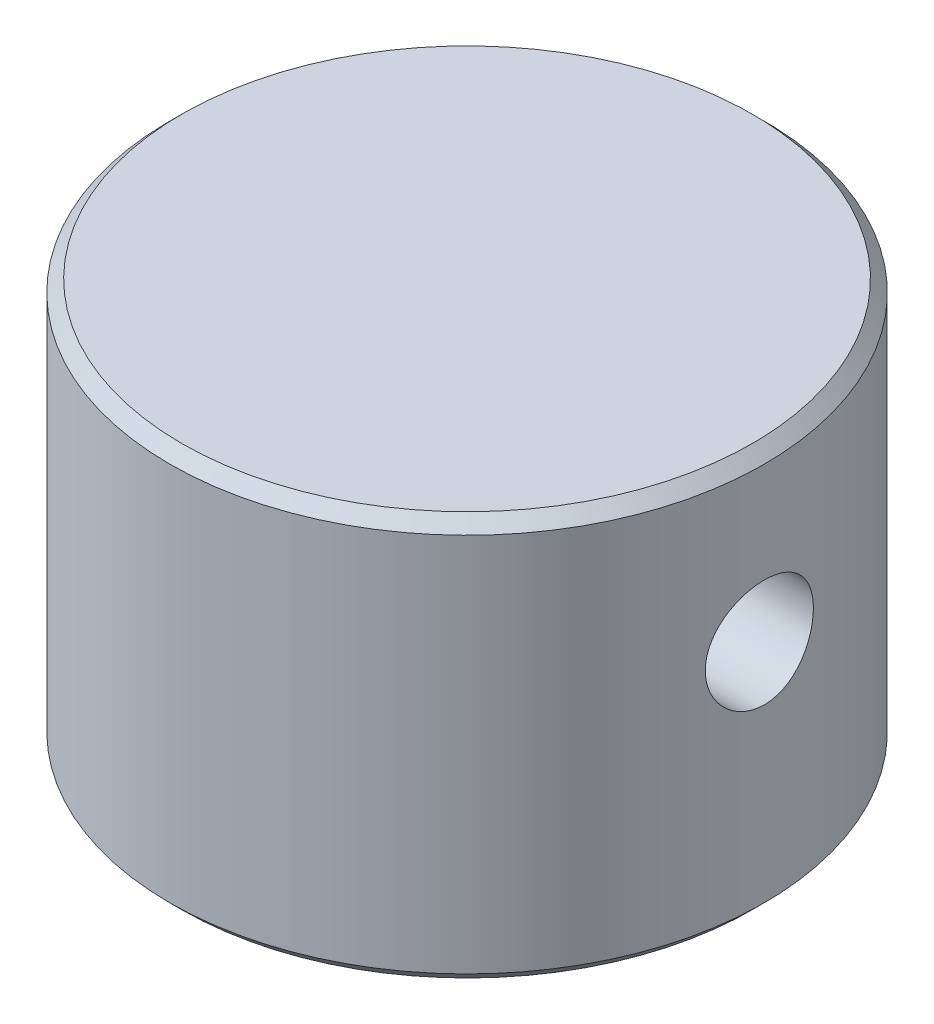
SolidWorks part; units mm, degrees
material "ASTM A36 Steel"
ref_plane "Front Plane" through (0, 0, 0) normal (0, 0, 1) x (1, 0, 0)
ref_plane "Top Plane" through (0, 0, 0) normal (0, 1, 0) x (1, 0, 0)
ref_plane "Right Plane" through (0, 0, 0) normal (1, 0, 0) x (0, 0, -1)
sketch "Sketch2" plane through (0, 0, 0) normal (0, 1, 0) x (1, 0, 0)
  circle A0 centre (0, 0) radius 12.45
  dimension "D1" = 24.9
extrude "Boss-Extrude1" add sketch "Sketch2" along normal blind 16.915
sketch "Sketch3" plane through (0, 16.915, 0) normal (0, 1, 0) x (1, 0, 0)
  line L0 (0, 0) -> (-12.45, 0) construction
  line L1 (-12.45, 0) -> (12.45, 0) construction
  circle A0 centre (0, 0) radius 12.45 construction
ref_plane "Plane1" through (12.45, 0, 0) normal (1, 0, 0) x (0, 0, -1)
sketch "Sketch6" plane through (0, 0, 0) normal (0, -1, 0) x (1, 0, 0)
  circle A0 centre (0, 0) radius 11
  dimension "D1" = 22
extrude "Cut-Extrude2" cut sketch "Sketch6" against normal blind 15.5
sketch "Sketch7" plane through (0, 15.5, 0) normal (0, -1, 0) x (1, 0, 0)
  line L0 (0, 11) -> (0, -11) construction
  line L1 (-4, 10.247) -> (-4, -10.247)
  line L2 (4, 10.247) -> (4, -10.247)
  circle A0 centre (0, 0) radius 11 construction
  circle A1 centre (0, 0) radius 11 construction
  arc A2 (-4, 10.247) -> (-4, -10.247) centre (0, 0) ccw
  arc A3 (4, -10.247) -> (4, 10.247) centre (0, 0) ccw
  dimension "D1" = 4
extrude "Boss-Extrude2" add sketch "Sketch7" along normal blind 9
sketch "Sketch5" plane through (12.45, 0, 0) normal (1, 0, 0) x (0, 0, -1)
  line L0 (12.45, 16.915) -> (-12.45, 16.915) construction
  circle A0 centre (0, 9.95) radius 2.265
  dimension "D1" = 6.965
  dimension "D2" = 4.53
  dimension "D3" = 9.95
extrude "Cut-Extrude1" cut sketch "Sketch5" against normal through all
chamfer "Chamfer1" distance 0.5 angle 45 1 edges at (0, 16.915, 12.45)
chamfer "Chamfer2" distance 0.5 angle 45 1 edges at (0, 0, 12.45)
sketch "Sketch8" plane through (-4, 0, 0) normal (1, 0, 0) x (0, 0, -1)
  line L0 (0, 9.95) -> (0, 15.5) construction
  line L1 (10.247, 15.5) -> (-10.247, 15.5) construction
  dimension "D1" = 5.55
